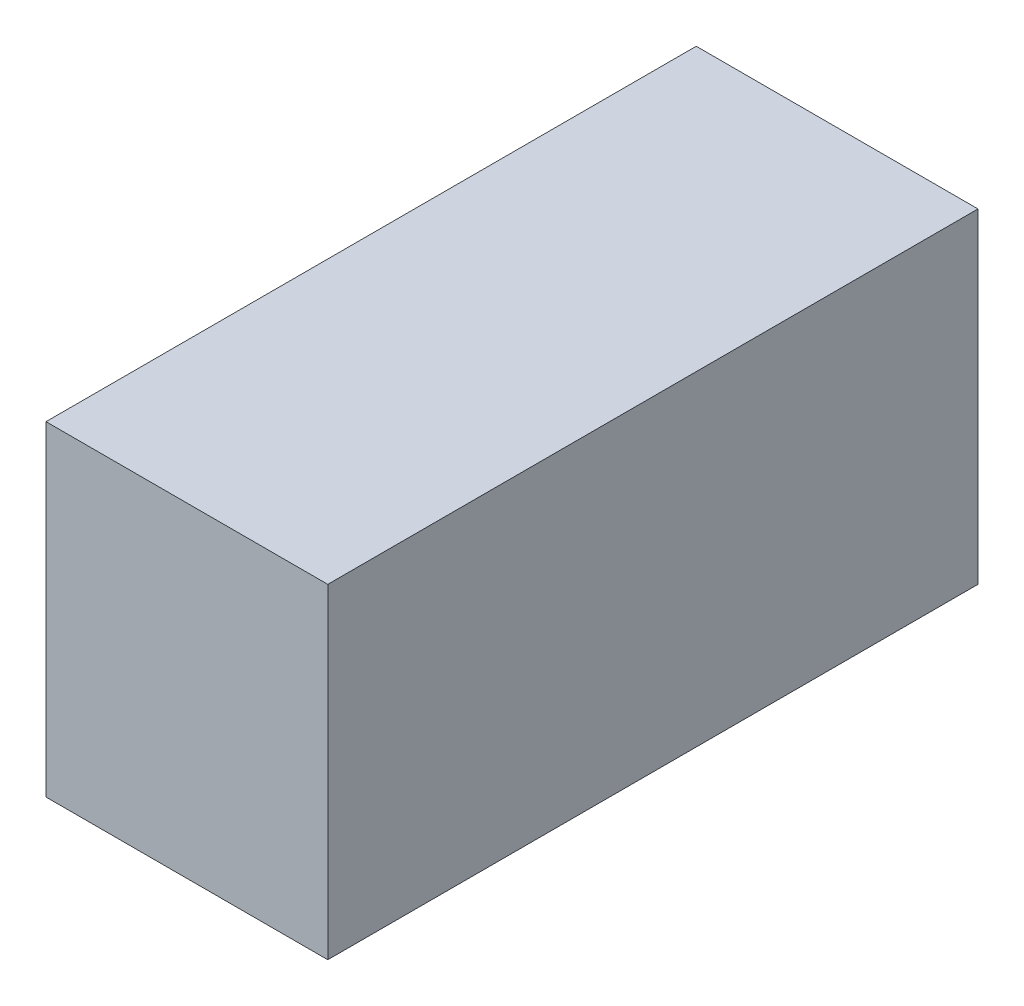
SolidWorks part; units mm, degrees
ref_plane "Front Plane" through (0, 0, 0) normal (0, 0, 1) x (1, 0, 0)
ref_plane "Top Plane" through (0, 0, 0) normal (0, 1, 0) x (1, 0, 0)
ref_plane "Right Plane" through (0, 0, 0) normal (1, 0, 0) x (0, 0, -1)
sketch "Sketch1" plane through (0, 0, 0) normal (0, 1, 0) x (1, 0, 0)
  line L1 (-9.6782, 9.0576) -> (3.3218, 9.0576)
  line L2 (-9.6782, 9.0576) -> (-9.6782, -20.9424)
  line L3 (-9.6782, -20.9424) -> (3.3218, -20.9424)
  line L4 (3.3218, 9.0576) -> (3.3218, -20.9424)
  dimension "D1" = 13
  dimension "D2" = 30
extrude "Boss-Extrude1" add sketch "Sketch1" along normal blind 15
